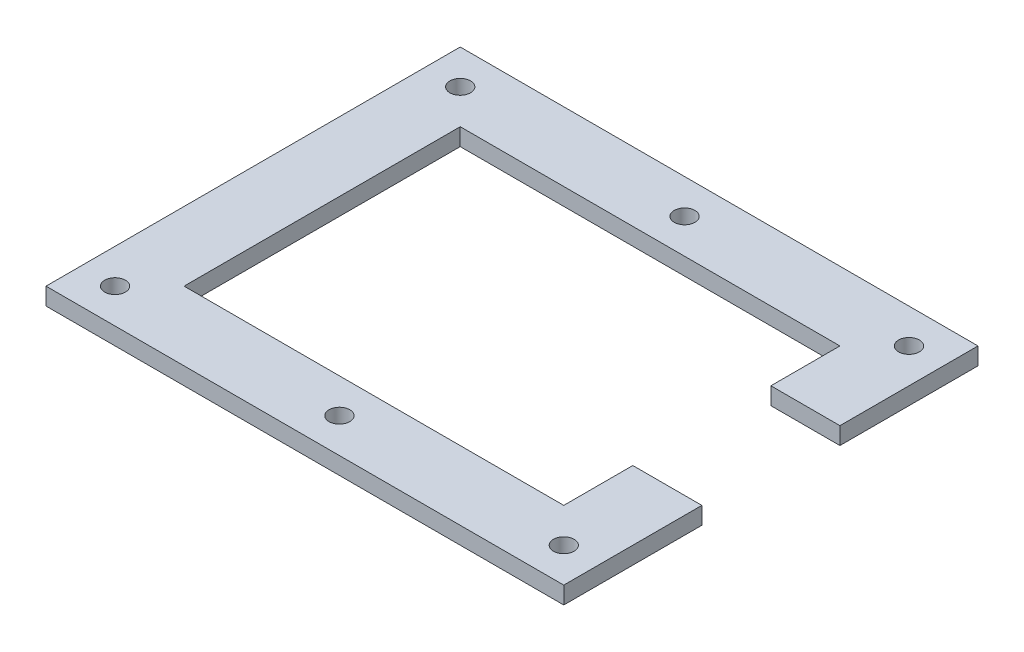
SolidWorks part; units mm, degrees
ref_plane "前视基准面" through (0, 0, 0) normal (0, 0, 1) x (1, 0, 0)
ref_plane "上视基准面" through (0, 0, 0) normal (0, 1, 0) x (1, 0, 0)
ref_plane "右视基准面" through (0, 0, 0) normal (1, 0, 0) x (0, 0, -1)
sketch "草图1" plane through (0, 0, 0) normal (0, 1, 0) x (1, 0, 0)
  line L0 (0, -30) -> (0, 30)
  line L1 (0, 30) -> (75, 30)
  line L2 (75, 30) -> (75, 10)
  line L3 (75, 10) -> (65, 10)
  line L4 (65, 10) -> (65, 20)
  line L5 (65, 20) -> (10, 20)
  line L6 (10, 20) -> (10, -20)
  line L7 (10, -20) -> (65, -20)
  line L8 (65, -20) -> (65, -10)
  line L9 (65, -10) -> (75, -10)
  line L10 (75, -10) -> (75, -30)
  line L11 (75, -30) -> (0, -30)
  point P4 (0, 0)
  dimension "D1" = 75
  dimension "D2" = 75
  dimension "D3" = 10
  dimension "D4" = 10
  dimension "D5" = 60
  dimension "D6" = 10
  dimension "D7" = 10
  dimension "D8" = 10
  dimension "D9" = 10
  dimension "D10" = 10
extrude "凸台-拉伸2" add sketch "草图1" along normal blind 2.5
sketch "草图2" plane through (0, 0, 0) normal (0, 1, 0) x (1, 0, 0)
  line L0 (0, 30) -> (0, -30) construction
  line L2 (75, 30) -> (0, 30) construction
  line L3 (37.5, 24.8609) -> (37.5, 16.1676) construction
  line L4 (0, 0) -> (12.8412, 0) construction
  line L5 (75, 10) -> (75, 30) construction
  circle A0 centre (5, 25) radius 1.5
  circle A1 centre (70, 25) radius 1.5
  circle A2 centre (70, -25) radius 1.5
  circle A3 centre (5, -25) radius 1.5
  circle A4 centre (37.5, -25) radius 1.5
  circle A5 centre (37.5, 25) radius 1.5
  dimension "D1" = 3
  dimension "D2" = 5
  dimension "D3" = 5
  dimension "D4" = 37.5
  dimension "D5" = 2
extrude "切除-拉伸1" cut sketch "草图2" along normal through all
